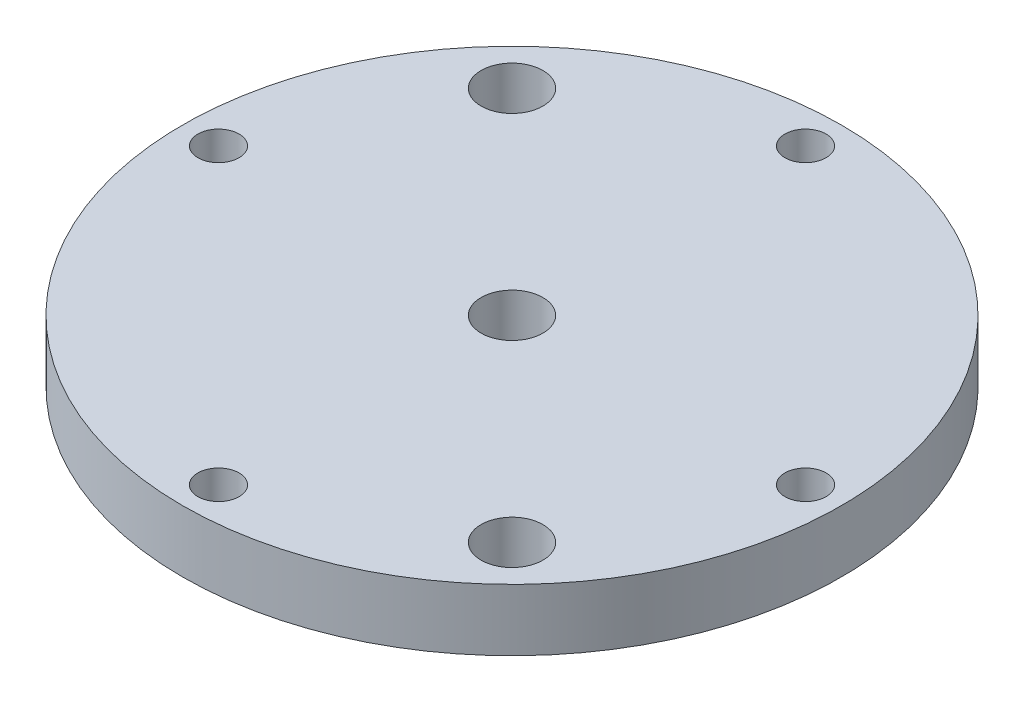
SolidWorks part; units mm, degrees
ref_plane "Plano frontal" through (0, 0, 0) normal (0, 0, 1) x (1, 0, 0)
ref_plane "Plano superior" through (0, 0, 0) normal (0, 1, 0) x (1, 0, 0)
ref_plane "Plano direito" through (0, 0, 0) normal (1, 0, 0) x (0, 0, -1)
sketch "Esboço1" plane through (0, 0, 0) normal (0, 1, 0) x (1, 0, 0)
  circle A0 centre (0, 0) radius 32
  circle A1 centre (0, 0) radius 3
  circle A2 centre (0, 28.5) radius 2
  circle A5 centre (28.5, 0) radius 2
  circle A6 centre (0, -28.5) radius 2
  circle A7 centre (-28.5, 0) radius 2
  circle A8 centre (-19.0919, 19.0919) radius 3
  circle A9 centre (19.0919, -19.0919) radius 3
  point P15 (0, 0)
  dimension "D2" = 6
  dimension "D3" = 28.5
  dimension "D4" = 28.5
  dimension "D6" = 6
  dimension "D10" = 64
  dimension "D11" = 45
  dimension "D16" = 28.5
  dimension "D5" = 45
  dimension "D7" = 28.5
  dimension "D8" = 27
  dimension "D9" = 27
  dimension "D12" = 45
  dimension "D13" = 90
  dimension "D14" = 45
  dimension "D15" = 90
extrude "Ressalto-extrusão3" add sketch "Esboço1" along normal blind 6
